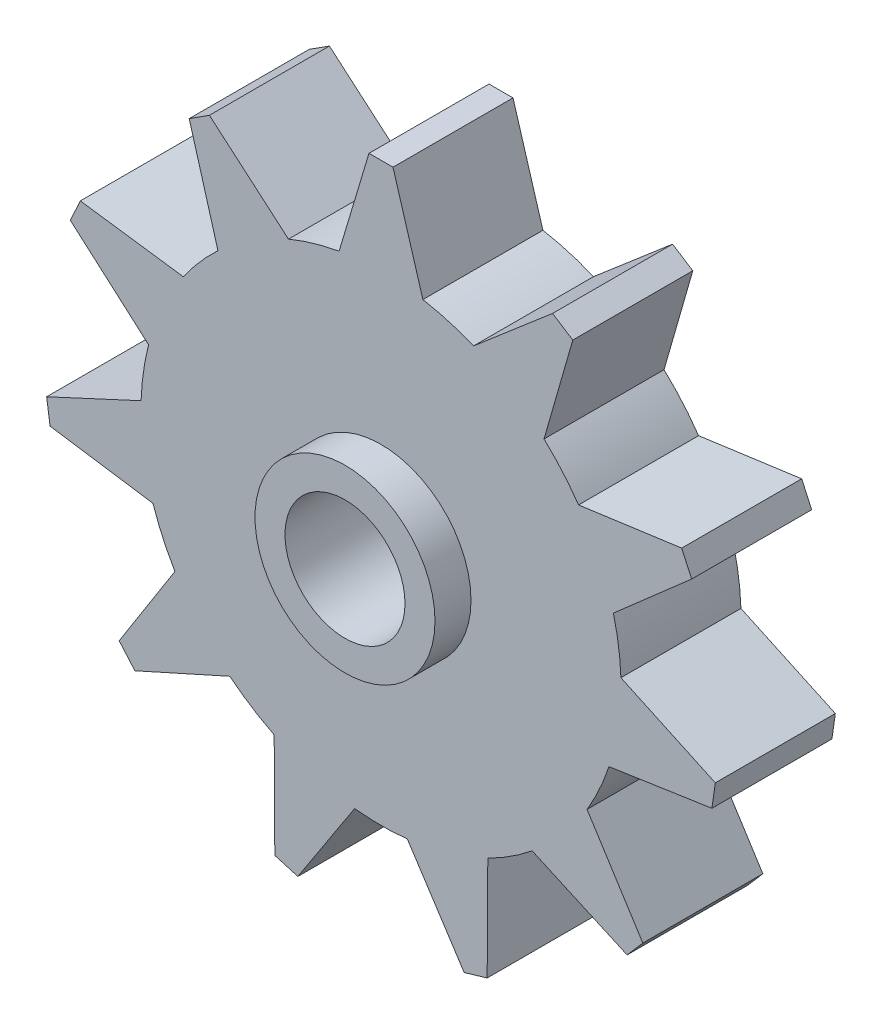
SolidWorks part; units mm, degrees
ref_plane "Front Plane" through (0, 0, 0) normal (0, 0, 1) x (1, 0, 0)
ref_plane "Top Plane" through (0, 0, 0) normal (0, 1, 0) x (1, 0, 0)
ref_plane "Right Plane" through (0, 0, 0) normal (1, 0, 0) x (0, 0, -1)
sketch "Sketch1" plane through (0, 0, 0) normal (0, 0, 1) x (1, 0, 0)
  circle A0 centre (0, 0) radius 20
  dimension "D1" = 40
extrude "Boss-Extrude1" add sketch "Sketch1" along normal blind 10
sketch "Sketch2" plane through (0, 0, 10) normal (0, 0, 1) x (1, 0, 0)
  circle A0 centre (0, 0) radius 7.5
  dimension "D1" = 15
extrude "Boss-Extrude2" add sketch "Sketch2" along normal blind 3 and the other way blind 13
sketch "Sketch3" plane through (0, 0, 13) normal (0, 0, 1) x (1, 0, 0)
  circle A0 centre (0, 0) radius 5
  dimension "D1" = 10
extrude "Cut-Extrude2" cut sketch "Sketch3" against normal through all both and the other way through all
sketch "Sketch4" plane through (0, 0, 10) normal (0, 0, 1) x (1, 0, 0)
  line L0 (0, 0) -> (0, 20) construction
  line L1 (0, 20) -> (0, 28) construction
  line L2 (-1, 28) -> (1, 28)
  line L3 (1, 28) -> (4, 18)
  line L4 (4, 18) -> (-4, 18)
  line L5 (-4, 18) -> (-1, 28)
  line L6 (0, 20) -> (0, 18) construction
  line L7 (6.3665, 17.3051) -> (14.2967, 24.0957)
  line L8 (14.2967, 24.0957) -> (15.9792, 23.0145)
  line L9 (15.9792, 23.0145) -> (13.0965, 12.98)
  line L10 (13.0965, 12.98) -> (6.3665, 17.3051)
  line L11 (14.7117, 11.116) -> (25.0543, 12.5413)
  line L12 (25.0543, 12.5413) -> (25.8851, 10.722)
  line L13 (25.8851, 10.722) -> (18.035, 3.8389)
  line L14 (18.035, 3.8389) -> (14.7117, 11.116)
  line L15 (18.386, 1.3976) -> (27.8573, -2.995)
  line L16 (27.8573, -2.995) -> (27.5727, -4.9746)
  line L17 (27.5727, -4.9746) -> (17.2475, -6.521)
  line L18 (17.2475, -6.521) -> (18.386, 1.3976)
  line L19 (16.2229, -8.7645) -> (21.8158, -17.5804)
  line L20 (21.8158, -17.5804) -> (20.5061, -19.0919)
  line L21 (20.5061, -19.0919) -> (10.984, -14.8105)
  line L22 (10.984, -14.8105) -> (16.2229, -8.7645)
  line L23 (8.9092, -16.1439) -> (8.848, -26.5841)
  line L24 (8.848, -26.5841) -> (6.929, -27.1475)
  line L25 (6.929, -27.1475) -> (1.2332, -18.3978)
  line L26 (1.2332, -18.3978) -> (8.9092, -16.1439)
  line L27 (-1.2332, -18.3978) -> (-6.929, -27.1475)
  line L28 (-6.929, -27.1475) -> (-8.848, -26.5841)
  line L29 (-8.848, -26.5841) -> (-8.9092, -16.1439)
  line L30 (-8.9092, -16.1439) -> (-1.2332, -18.3978)
  line L31 (-10.984, -14.8105) -> (-20.5061, -19.0919)
  line L32 (-20.5061, -19.0919) -> (-21.8158, -17.5804)
  line L33 (-21.8158, -17.5804) -> (-16.2229, -8.7645)
  line L34 (-16.2229, -8.7645) -> (-10.984, -14.8105)
  line L35 (-17.2475, -6.521) -> (-27.5727, -4.9746)
  line L36 (-27.5727, -4.9746) -> (-27.8573, -2.995)
  line L37 (-27.8573, -2.995) -> (-18.386, 1.3976)
  line L38 (-18.386, 1.3976) -> (-17.2475, -6.521)
  line L39 (-18.035, 3.8389) -> (-25.8851, 10.722)
  line L40 (-25.8851, 10.722) -> (-25.0543, 12.5413)
  line L41 (-25.0543, 12.5413) -> (-14.7117, 11.116)
  line L42 (-14.7117, 11.116) -> (-18.035, 3.8389)
  line L43 (-13.0965, 12.98) -> (-15.9792, 23.0145)
  line L44 (-15.9792, 23.0145) -> (-14.2967, 24.0957)
  line L45 (-14.2967, 24.0957) -> (-6.3665, 17.3051)
  line L46 (-6.3665, 17.3051) -> (-13.0965, 12.98)
  circle A0 centre (0, 0) radius 20 construction
  point P11 (0, 28)
  point P57 (0, 0)
  dimension "D1" = 8
  dimension "D2" = 8
  dimension "D3" = 2
  dimension "D4" = 2
  dimension "D5" = 11
extrude "Boss-Extrude3" add sketch "Sketch4" against normal blind 10
